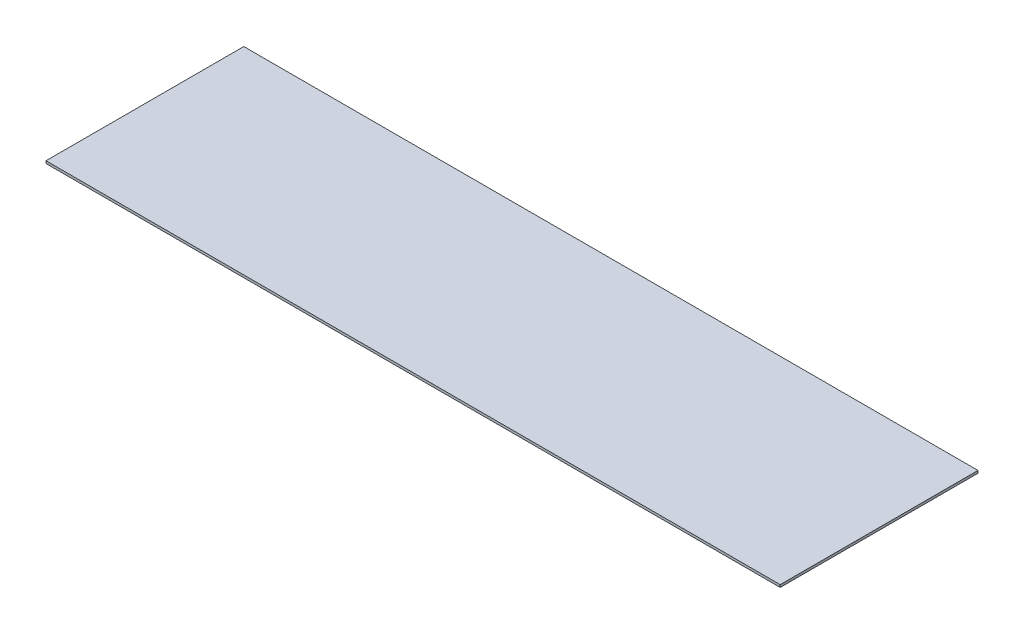
SolidWorks part; units mm, degrees
ref_plane "Front Plane" through (0, 0, 0) normal (0, 0, 1) x (1, 0, 0)
ref_plane "Top Plane" through (0, 0, 0) normal (0, 1, 0) x (1, 0, 0)
ref_plane "Right Plane" through (0, 0, 0) normal (1, 0, 0) x (0, 0, -1)
sketch "Sketch1" plane through (0, 0, 0) normal (0, 1, 0) x (1, 0, 0)
  line L1 (-75, 20.205) -> (75, 20.205)
  line L2 (-75, 20.205) -> (-75, -20.205)
  line L3 (-75, -20.205) -> (75, -20.205)
  line L4 (75, 20.205) -> (75, -20.205)
  line L5 (-75, 20.205) -> (75, -20.205) construction
  line L6 (-75, -20.205) -> (75, 20.205) construction
  point P0 (0, 0)
  dimension "D1" = 40.41
  dimension "D2" = 150
extrude "Boss-Extrude1" add sketch "Sketch1" along normal blind 0.5
